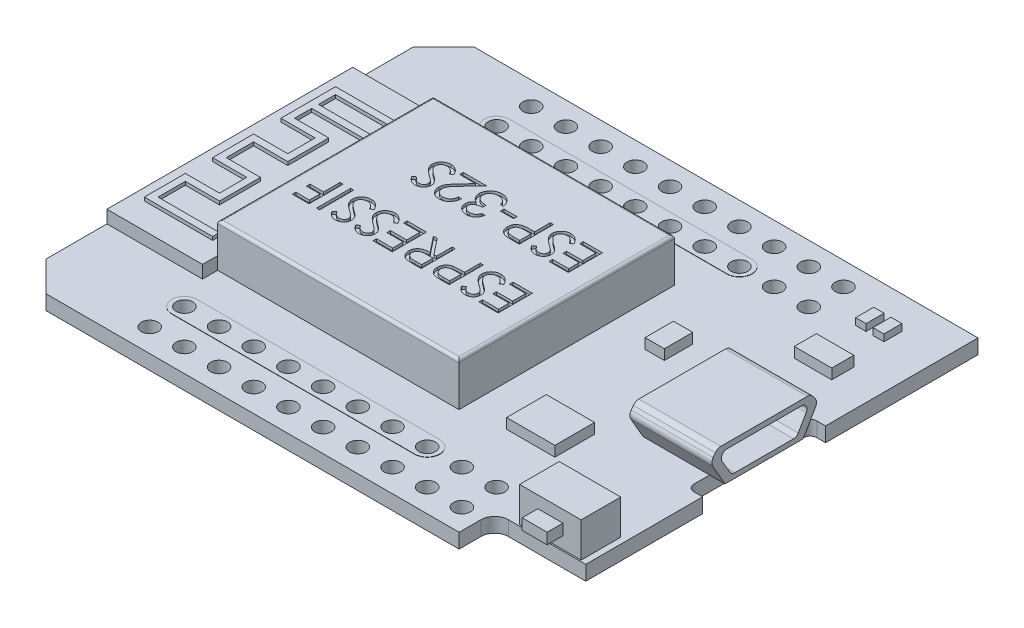
SolidWorks part; units mm, degrees
ref_plane "Front Plane" through (0, 0, 0) normal (0, 0, 1) x (1, 0, 0)
ref_plane "Top Plane" through (0, 0, 0) normal (0, 1, 0) x (1, 0, 0)
ref_plane "Right Plane" through (0, 0, 0) normal (1, 0, 0) x (0, 0, -1)
sketch "Sketch1" plane through (0, 0, 0) normal (0, 1, 0) x (1, 0, 0)
  line L1 (0, 0) -> (39.12, 0)
  line L2 (0, 0) -> (0, 31.32)
  line L3 (0, 31.32) -> (39.12, 31.32)
  line L4 (39.12, 0) -> (39.12, 31.32)
  dimension "D1" = 31.32
  dimension "D2" = 39.12
extrude "Boss-Extrude1" add sketch "Sketch1" along normal blind 1.07
chamfer "Chamfer1" distance 2.2 angle 45 2 edges at (0, 0.535, -31.32) (0, 0.535, 0)
sketch "Sketch2" plane through (0, 1.07, 0) normal (0, 1, 0) x (1, 0, 0)
  line L1 (39.12, 0) -> (32.45, 0)
  line L2 (39.12, 0) -> (39.12, 2.6)
  line L3 (39.12, 2.6) -> (32.45, 2.6)
  line L4 (32.45, 0) -> (32.45, 2.6)
  dimension "D1" = 6.67
  dimension "D2" = 2.6
extrude "Cut-Extrude1" cut sketch "Sketch2" against normal through all
fillet "Fillet1" radius 1 1 edges at (32.45, 0.535, -2.6)
sketch "Sketch3" plane through (0, 1.07, 0) normal (0, 1, 0) x (1, 0, 0)
  line L0 (0, 15.66) -> (39.12, 15.66) construction
  line L1 (7, 7.77) -> (24.67, 7.77)
  line L2 (7, 7.77) -> (7, 23.55)
  line L3 (7, 23.55) -> (24.67, 23.55)
  line L4 (24.67, 7.77) -> (24.67, 23.55)
  line L5 (0, 29.12) -> (0, 2.2) construction
  line L6 (39.12, 2.6) -> (39.12, 31.32) construction
  point P10 (7, 15.66)
  dimension "D1" = 15.78
  dimension "D2" = 17.67
  dimension "D3" = 7
extrude "Boss-Extrude2" add sketch "Sketch3" along normal blind 3.17
sketch "Sketch4" plane through (0, 1.07, 0) normal (0, 1, 0) x (1, 0, 0)
  line L0 (7, 15.66) -> (39.12, 15.66) construction
  line L1 (0, 29.12) -> (0, 2.2) construction
  line L2 (39.12, 2.6) -> (39.12, 31.32) construction
  line L3 (7, 23.55) -> (7, 7.77) construction
  line L4 (0, 24.66) -> (7, 24.66)
  line L5 (0, 24.66) -> (0, 6.66)
  line L7 (7, 24.66) -> (7, 6.66)
  line L8 (0, 6.66) -> (7, 6.66)
extrude "Boss-Extrude3" add sketch "Sketch4" along normal blind 0.93
sketch "Sketch5" plane through (0, 1.07, 0) normal (0, 1, 0) x (1, 0, 0)
  line L0 (0, 15.66) -> (39.12, 15.66) construction
  line L1 (0, 24.66) -> (0, 6.66) construction
  line L2 (39.12, 2.6) -> (39.12, 31.32) construction
  line L3 (8.1, 31.32) -> (8.1, 0) construction
  line L4 (39.12, 31.32) -> (2.2, 31.32) construction
  line L5 (2.2, 0) -> (32.45, 0) construction
  line L6 (39.12, 29.63) -> (0, 29.63) construction
  line L7 (0, 29.12) -> (0, 24.66) construction
  line L8 (0, 27.09) -> (39.12, 27.09) construction
  circle A1 centre (8.1, 29.63) radius 0.61
  circle A2 centre (8.1, 27.09) radius 0.61
  circle A3 centre (10.64, 29.63) radius 0.61
  circle A4 centre (10.64, 27.09) radius 0.61
  circle A5 centre (13.18, 29.63) radius 0.61
  circle A6 centre (13.18, 27.09) radius 0.61
  circle A7 centre (15.72, 29.63) radius 0.61
  circle A8 centre (15.72, 27.09) radius 0.61
  circle A9 centre (18.26, 29.63) radius 0.61
  circle A10 centre (18.26, 27.09) radius 0.61
  circle A11 centre (20.8, 29.63) radius 0.61
  circle A12 centre (20.8, 27.09) radius 0.61
  circle A13 centre (23.34, 29.63) radius 0.61
  circle A14 centre (23.34, 27.09) radius 0.61
  circle A15 centre (25.88, 29.63) radius 0.61
  circle A16 centre (25.88, 27.09) radius 0.61
  circle A17 centre (28.42, 29.63) radius 0.61
  circle A18 centre (28.42, 27.09) radius 0.61
  circle A19 centre (30.96, 29.63) radius 0.61
  circle A20 centre (30.96, 27.09) radius 0.61
  circle A21 centre (30.96, 4.23) radius 0.61
  circle A22 centre (30.96, 1.69) radius 0.61
  circle A23 centre (28.42, 4.23) radius 0.61
  circle A24 centre (28.42, 1.69) radius 0.61
  circle A25 centre (25.88, 4.23) radius 0.61
  circle A26 centre (25.88, 1.69) radius 0.61
  circle A27 centre (23.34, 4.23) radius 0.61
  circle A28 centre (23.34, 1.69) radius 0.61
  circle A29 centre (20.8, 4.23) radius 0.61
  circle A30 centre (20.8, 1.69) radius 0.61
  circle A31 centre (18.26, 4.23) radius 0.61
  circle A32 centre (18.26, 1.69) radius 0.61
  circle A33 centre (15.72, 4.23) radius 0.61
  circle A34 centre (15.72, 1.69) radius 0.61
  circle A35 centre (13.18, 4.23) radius 0.61
  circle A36 centre (13.18, 1.69) radius 0.61
  circle A37 centre (10.64, 4.23) radius 0.61
  circle A38 centre (10.64, 1.69) radius 0.61
  circle A39 centre (8.1, 4.23) radius 0.61
  circle A40 centre (8.1, 1.69) radius 0.61
  dimension "D1" = 1.22
  dimension "D2" = 8.1
  dimension "D3" = 13.97
  dimension "D4" = 2.54
  dimension "D5" = 2
  dimension "D6" = 10
extrude "Cut-Extrude2" cut sketch "Sketch5" against normal through all
fillet "Fillet2" radius 0.2 4 edges at (15.835, 4.24, -23.55) (24.67, 4.24, -15.66) (15.835, 4.24, -7.77) (7, 4.24, -15.66)
sketch "Sketch7" plane through (0, 1.07, 0) normal (0, 1, 0) x (1, 0, 0)
  line L0 (8.1, 27.7) -> (8.1, 26.48) construction
  line L1 (8.1, 30.24) -> (8.1, 29.02) construction
  circle A0 centre (8.1, 27.09) radius 0.61 construction
  circle A1 centre (8.1, 29.63) radius 0.61 construction
  point P5 (8.1, 27.09)
  point P11 (8.1, 29.63)
sketch "Sketch8" plane through (0, 1.07, 0) normal (0, 1, 0) x (1, 0, 0)
  line L1 (34.18, 5.6) -> (38.68, 5.6)
  line L2 (34.18, 5.6) -> (34.18, 2.7)
  line L4 (38.68, 5.6) -> (38.68, 2.7)
  line L5 (39.12, 2.6) -> (39.12, 31.32) construction
  line L6 (34.18, 2.7) -> (38.68, 2.7)
  line L7 (39.12, 2.6) -> (33.45, 2.6) construction
  dimension "D1" = 4.5
  dimension "D2" = 0.1
  dimension "D3" = 0.44
  dimension "D4" = 2.9
extrude "Boss-Extrude4" add sketch "Sketch8" along normal blind 2.55
sketch "Sketch9" plane through (0, 0, -2.7) normal (0, 0, 1) x (1, 0, 0)
  line L0 (38.68, 2.345) -> (34.18, 2.345) construction
  line L1 (38.68, 3.62) -> (38.68, 1.07) construction
  line L2 (34.18, 3.62) -> (34.18, 1.07) construction
  line L4 (35.515, 1.945) -> (37.345, 1.945)
  line L5 (35.515, 1.945) -> (35.515, 2.745)
  line L6 (35.515, 2.745) -> (37.345, 2.745)
  line L7 (37.345, 1.945) -> (37.345, 2.745)
  line L8 (35.515, 1.945) -> (37.345, 2.745) construction
  line L9 (35.515, 2.745) -> (37.345, 1.945) construction
  point P6 (36.43, 2.345)
  dimension "D1" = 1.83
  dimension "D2" = 0.8
extrude "Boss-Extrude5" add sketch "Sketch9" along normal blind 1.15
sketch "Sketch10" plane through (0, 0, 0) normal (0, -1, 0) x (1, 0, 0)
  line L0 (0, -15.66) -> (37.99, -15.66) construction
  line L1 (0, -29.12) -> (0, -2.2) construction
  line L3 (39.12, -20.16) -> (38.49, -20.16)
  line L5 (39.12, -20.16) -> (39.12, -11.16)
  line L6 (39.12, -11.16) -> (38.49, -11.16)
  line L7 (37.99, -19.66) -> (37.99, -11.66)
  arc A0 (37.99, -19.66) -> (38.49, -20.16) centre (38.49, -19.66) ccw
  arc A1 (38.49, -11.16) -> (37.99, -11.66) centre (38.49, -11.66) ccw
  point P5 (37.99, -20.16)
  point P13 (37.99, -11.16)
  dimension "D3" = 0.5
  dimension "D1" = 1.13
  dimension "D2" = 9
extrude "Cut-Extrude3" cut sketch "Sketch10" against normal through all
sketch "Sketch11" plane through (0, 1.07, 0) normal (0, 1, 0) x (1, 0, 0)
  line L0 (37.99, 15.66) -> (0, 15.66) construction
  line L1 (37.99, 11.66) -> (37.99, 19.66) construction
  line L2 (0, 24.66) -> (0, 6.66) construction
  line L3 (39.12, 20.16) -> (39.12, 11.16) construction
  line L4 (37.99, 11.73) -> (39.12, 11.73)
  line L7 (37.99, 19.59) -> (39.12, 19.59)
  line L8 (39.12, 11.73) -> (39.12, 19.59)
  line L10 (37.99, 19.59) -> (33.12, 19.59)
  line L12 (37.99, 11.73) -> (33.12, 11.73)
  line L13 (33.12, 19.59) -> (33.12, 11.73)
  dimension "D1" = 7.86
  dimension "D2" = 6
extrude "Boss-Extrude6" add sketch "Sketch11" along normal blind 2.54
sketch "Sketch12" plane through (39.12, 0, 0) normal (1, 0, 0) x (0, 0, -1)
  line L0 (15.66, 3.61) -> (15.66, 1.07) construction
  line L1 (11.73, 3.61) -> (19.59, 3.61) construction
  line L2 (11.73, 1.07) -> (19.59, 1.07) construction
  line L3 (19.59, 2.9231) -> (18.5201, 1.07)
  line L4 (11.73, 3.61) -> (11.73, 1.07) construction
  line L5 (11.73, 2.9231) -> (12.7999, 1.07)
  line L6 (11.73, 1.07) -> (19.59, 1.07) construction
  line L7 (19.59, 1.07) -> (18.5201, 1.07)
  line L8 (11.73, 2.9231) -> (11.73, 1.07)
  line L9 (11.73, 1.07) -> (12.7999, 1.07)
  line L10 (19.59, 2.9231) -> (19.59, 1.07)
  dimension "D1" = 60
extrude "Cut-Extrude4" cut sketch "Sketch12" against normal up to next
sketch "Sketch13" plane through (39.12, 0, 0) normal (1, 0, 0) x (0, 0, -1)
  line L0 (11.73, 2.9231) -> (12.2398, 3.61)
  line L1 (11.73, 3.61) -> (19.59, 3.61) construction
  line L2 (12.2398, 3.61) -> (11.73, 3.61)
  line L3 (11.73, 3.61) -> (11.73, 2.9231) construction
  line L4 (11.73, 3.61) -> (11.73, 2.9231)
  line L5 (15.66, 1.07) -> (15.66, 3.61) construction
  line L6 (12.7999, 1.07) -> (18.5201, 1.07) construction
  line L7 (19.0802, 3.61) -> (19.59, 3.61)
  line L8 (19.59, 2.9231) -> (19.0802, 3.61)
  line L9 (19.59, 3.61) -> (19.59, 2.9231)
extrude "Cut-Extrude5" cut sketch "Sketch13" against normal up to next
fillet "Fillet3" radius 0.5 4 edges at (36.12, 2.9231, -19.59) (36.12, 3.61, -19.0802) (36.12, 3.61, -12.2398) (36.12, 2.9231, -11.73)
sketch "Sketch15" plane through (0, 0, 0) normal (0, -1, 0) x (1, 0, 0)
  line L0 (7.49, -1.69) -> (8.71, -1.69) construction
  line L1 (30.35, -1.69) -> (31.57, -1.69) construction
  line L2 (30.35, -4.23) -> (31.57, -4.23) construction
  line L3 (7.49, -4.23) -> (8.71, -4.23) construction
  line L4 (7.49, -27.09) -> (8.71, -27.09) construction
  line L5 (7.49, -29.63) -> (8.71, -29.63) construction
  line L6 (30.35, -27.09) -> (31.57, -27.09) construction
  line L7 (30.35, -29.63) -> (31.57, -29.63) construction
  circle A0 centre (8.1, -1.69) radius 0.61 construction
  circle A1 centre (30.96, -1.69) radius 0.61 construction
  circle A2 centre (30.96, -4.23) radius 0.61 construction
  circle A3 centre (8.1, -4.23) radius 0.61 construction
  circle A4 centre (8.1, -27.09) radius 0.61 construction
  circle A5 centre (8.1, -29.63) radius 0.61 construction
  circle A6 centre (30.96, -27.09) radius 0.61 construction
  circle A7 centre (30.96, -29.63) radius 0.61 construction
  point P20 (8.1, -1.69)
  point P21 (8.1, -4.23)
  point P22 (30.96, -1.69)
  point P23 (30.96, -4.23)
  point P44 (8.1, -27.09)
  point P45 (8.1, -29.63)
  point P46 (30.96, -27.09)
  point P47 (30.96, -29.63)
sketch "Sketch16" plane through (0, 4.24, 0) normal (0, 1, 0) x (1, 0, 0)
  line L0 (23.4654, 14.6629) -> (8.0101, 14.6629) construction
  text T0 "ESPRESSIF\r\nESP-32S" font "Century Gothic" height 2.5
extrude "Cut-Extrude6" cut sketch "Sketch16" against normal blind 0.2
sketch "Sketch17" plane through (0, 0, 0) normal (0, -1, 0) x (-1, 0, 0)
  line L0 (-31.57, 29.63) -> (-30.35, 29.63) construction
  line L1 (-31.57, 27.09) -> (-30.35, 27.09) construction
  line L2 (-8.71, 29.63) -> (-7.49, 29.63) construction
  line L3 (-8.71, 27.09) -> (-7.49, 27.09) construction
  line L4 (-31.57, 4.23) -> (-30.35, 4.23) construction
  line L5 (-31.57, 1.69) -> (-30.35, 1.69) construction
  line L6 (-8.71, 4.23) -> (-7.49, 4.23) construction
  line L7 (-8.71, 1.69) -> (-7.49, 1.69) construction
  circle A0 centre (-30.96, 29.63) radius 0.61 construction
  circle A1 centre (-30.96, 27.09) radius 0.61 construction
  circle A2 centre (-8.1, 29.63) radius 0.61 construction
  circle A3 centre (-8.1, 27.09) radius 0.61 construction
  circle A4 centre (-30.96, 4.23) radius 0.61 construction
  circle A5 centre (-30.96, 1.69) radius 0.61 construction
  circle A6 centre (-8.1, 4.23) radius 0.61 construction
  circle A7 centre (-8.1, 1.69) radius 0.61 construction
  point P20 (-8.1, 29.63)
  point P21 (-8.1, 27.09)
  point P22 (-30.96, 29.63)
  point P23 (-30.96, 27.09)
  point P44 (-30.96, 4.23)
  point P45 (-30.96, 1.69)
  point P46 (-8.1, 4.23)
  point P47 (-8.1, 1.69)
sketch "Sketch18" plane through (39.12, 0, 0) normal (1, 0, 0) x (0, 0, -1)
  line L0 (15.66, 3.61) -> (15.66, 1.07) construction
  line L1 (12.4914, 3.61) -> (18.8286, 3.61) construction
  line L2 (12.7999, 1.07) -> (18.5201, 1.07) construction
  line L3 (18.3922, 3.2228) -> (12.9278, 3.2228)
  line L4 (12.5814, 2.6228) -> (13.1588, 1.6228)
  line L5 (13.5052, 1.4228) -> (17.8148, 1.4228)
  line L6 (12.7999, 1.07) -> (11.8942, 2.6388) construction
  line L7 (18.7386, 2.6228) -> (18.1612, 1.6228)
  arc A0 (17.8148, 1.4228) -> (18.1612, 1.6228) centre (17.8148, 1.8228) ccw
  arc A1 (18.7386, 2.6228) -> (18.3922, 3.2228) centre (18.3922, 2.8228) ccw
  arc A2 (13.5052, 1.4228) -> (13.1588, 1.6228) centre (13.5052, 1.8228) cw
  arc A3 (12.5814, 2.6228) -> (12.9278, 3.2228) centre (12.9278, 2.8228) cw
  point P13 (15.66, 1.4228)
  point P14 (15.66, 3.2228)
  point P16 (18.0458, 1.4228)
  point P19 (19.085, 3.2228)
  point P22 (13.2742, 1.4228)
  point P25 (12.235, 3.2228)
  dimension "D3" = 0.4
  dimension "D1" = 1.8
  dimension "D2" = 3.425
extrude "Cut-Extrude7" cut sketch "Sketch18" against normal blind 4
sketch "Sketch20" plane through (0, 2, 0) normal (0, 1, 0) x (1, 0, 0)
  line L0 (5.8514, 22.55) -> (0.8514, 22.55)
  line L1 (0.8514, 22.55) -> (0.8514, 18.55)
  line L2 (0.8514, 18.55) -> (3.3514, 18.55)
  line L3 (3.3514, 18.55) -> (3.3514, 16.55)
  line L4 (3.3514, 16.55) -> (0.8514, 16.55)
  line L5 (0.8514, 16.55) -> (0.8514, 13.55)
  line L6 (0.8514, 13.55) -> (3.3514, 13.55)
  line L7 (3.3514, 13.55) -> (3.3514, 11.55)
  line L8 (3.3514, 11.55) -> (0.8514, 11.55)
  line L9 (0.8514, 11.55) -> (0.8514, 8.55)
  line L10 (0.8514, 8.55) -> (5.8514, 8.55)
  line L11 (5.8514, 8.55) -> (5.8514, 9.05)
  line L12 (5.8514, 9.05) -> (1.3514, 9.05)
  line L13 (1.3514, 9.05) -> (1.3514, 11.05)
  line L14 (1.3514, 11.05) -> (3.8514, 11.05)
  line L15 (3.8514, 11.05) -> (3.8514, 14.05)
  line L16 (3.8514, 14.05) -> (1.3514, 14.05)
  line L17 (1.3514, 14.05) -> (1.3514, 16.05)
  line L18 (1.3514, 16.05) -> (3.8514, 16.05)
  line L19 (3.8514, 16.05) -> (3.8514, 19.05)
  line L20 (3.8514, 19.05) -> (1.3514, 19.05)
  line L21 (1.3514, 19.05) -> (1.3514, 20.3)
  line L22 (1.3514, 22.05) -> (5.8514, 22.05)
  line L23 (5.8514, 22.05) -> (5.8514, 22.55)
  line L24 (1.3514, 20.8) -> (5.8514, 20.8)
  line L25 (5.8514, 20.8) -> (5.8514, 20.3)
  line L26 (5.8514, 20.3) -> (1.3514, 20.3)
  line L27 (1.3514, 20.8) -> (1.3514, 22.05)
  line L28 (7, 23.55) -> (24.67, 23.55) construction
  point P2 (3.6014, 22.05)
  point P25 (2.1014, 16.55)
  dimension "D1" = 0.5
  dimension "D2" = 0.5
  dimension "D3" = 0.5
  dimension "D4" = 0.5
  dimension "D5" = 0.5
  dimension "D6" = 0.5
  dimension "D7" = 0.5
  dimension "D8" = 0.5
  dimension "D9" = 0.5
  dimension "D10" = 0.5
  dimension "D11" = 0.5
  dimension "D12" = 5
  dimension "D13" = 5
  dimension "D14" = 2.5
  dimension "D15" = 2.5
  dimension "D16" = 3
  dimension "D17" = 3
  dimension "D18" = 3
  dimension "D19" = 3
  dimension "D20" = 4
  dimension "D21" = 0.5
  dimension "D22" = 1.25
  dimension "D23" = 1
extrude "Boss-Extrude7" add sketch "Sketch20" along normal blind 0.25
sketch "Sketch21" plane through (0, 1.07, 0) normal (0, 1, 0) x (1, 0, 0)
  line L1 (27.6615, 11.173) -> (31.193, 11.173)
  line L2 (27.6615, 11.173) -> (27.6615, 8.2648)
  line L3 (27.6615, 8.2648) -> (31.193, 8.2648)
  line L4 (31.193, 11.173) -> (31.193, 8.2648)
  line L5 (27.6615, 20.4794) -> (29.0741, 20.4794)
  line L6 (27.6615, 20.4794) -> (27.6615, 18.4021)
  line L7 (27.6615, 18.4021) -> (29.0741, 18.4021)
  line L8 (29.0741, 20.4794) -> (29.0741, 18.4021)
  line L9 (33.6857, 24.9248) -> (36.4278, 24.9248)
  line L10 (33.6857, 24.9248) -> (33.6857, 23.3045)
  line L11 (33.6857, 23.3045) -> (36.4278, 23.3045)
  line L12 (36.4278, 24.9248) -> (36.4278, 23.3045)
extrude "Boss-Extrude8" add sketch "Sketch21" along normal blind 0.75
sketch "Sketch22" plane through (0, 1.07, 0) normal (0, 1, 0) x (1, 0, 0)
  line L1 (33.8564, 28.9466) -> (34.6163, 28.9466)
  line L2 (33.8564, 28.9466) -> (33.8564, 27.6258)
  line L3 (33.8564, 27.6258) -> (34.6163, 27.6258)
  line L4 (34.6163, 28.9466) -> (34.6163, 27.6258)
  line L5 (35.1226, 28.9455) -> (35.9238, 28.9455)
  line L6 (35.1226, 28.9455) -> (35.1226, 27.6258)
  line L7 (35.1226, 27.6258) -> (35.9238, 27.6258)
  line L8 (35.9238, 28.9455) -> (35.9238, 27.6258)
extrude "Boss-Extrude9" add sketch "Sketch22" along normal blind 0.5
sketch "Sketch23" plane through (0, 1.07, 0) normal (0, 1, 0) x (1, 0, 0)
  line L0 (8.1, 27.09) -> (25.88, 27.09) construction
  line L1 (8.1, 28.0051) -> (25.88, 28.0051)
  line L2 (8.1, 26.1749) -> (25.88, 26.1749)
  line L3 (0, 15.66) -> (7, 15.66) construction
  line L4 (0, 24.66) -> (0, 6.66) construction
  line L5 (7, 7.77) -> (7, 23.55) construction
  line L6 (8.1, 4.23) -> (25.88, 4.23) construction
  line L9 (8.1, 3.3149) -> (25.88, 3.3149)
  line L10 (8.1, 5.1451) -> (25.88, 5.1451)
  arc A0 (8.1, 28.0051) -> (8.1, 26.1749) centre (8.1, 27.09) ccw
  arc A1 (25.88, 26.1749) -> (25.88, 28.0051) centre (25.88, 27.09) ccw
  circle A4 centre (8.1, 27.09) radius 0.61
  circle A5 centre (10.64, 27.09) radius 0.61
  circle A6 centre (13.18, 27.09) radius 0.61
  circle A7 centre (15.72, 27.09) radius 0.61
  circle A8 centre (18.26, 27.09) radius 0.61
  circle A9 centre (20.8, 27.09) radius 0.61
  circle A10 centre (23.34, 27.09) radius 0.61
  circle A11 centre (25.88, 27.09) radius 0.61
  circle A12 centre (25.88, 4.23) radius 0.61
  circle A13 centre (23.34, 4.23) radius 0.61
  circle A14 centre (20.8, 4.23) radius 0.61
  circle A15 centre (18.26, 4.23) radius 0.61
  circle A16 centre (15.72, 4.23) radius 0.61
  circle A17 centre (13.18, 4.23) radius 0.61
  circle A18 centre (10.64, 4.23) radius 0.61
  circle A19 centre (8.1, 4.23) radius 0.61
  arc A20 (8.1, 3.3149) -> (8.1, 5.1451) centre (8.1, 4.23) cw
  arc A21 (25.88, 5.1451) -> (25.88, 3.3149) centre (25.88, 4.23) cw
  point P4 (16.99, 27.09)
  point P47 (16.99, 4.23)
  dimension "D1" = 8
extrude "Boss-Extrude10" add sketch "Sketch23" along normal blind 0.02
